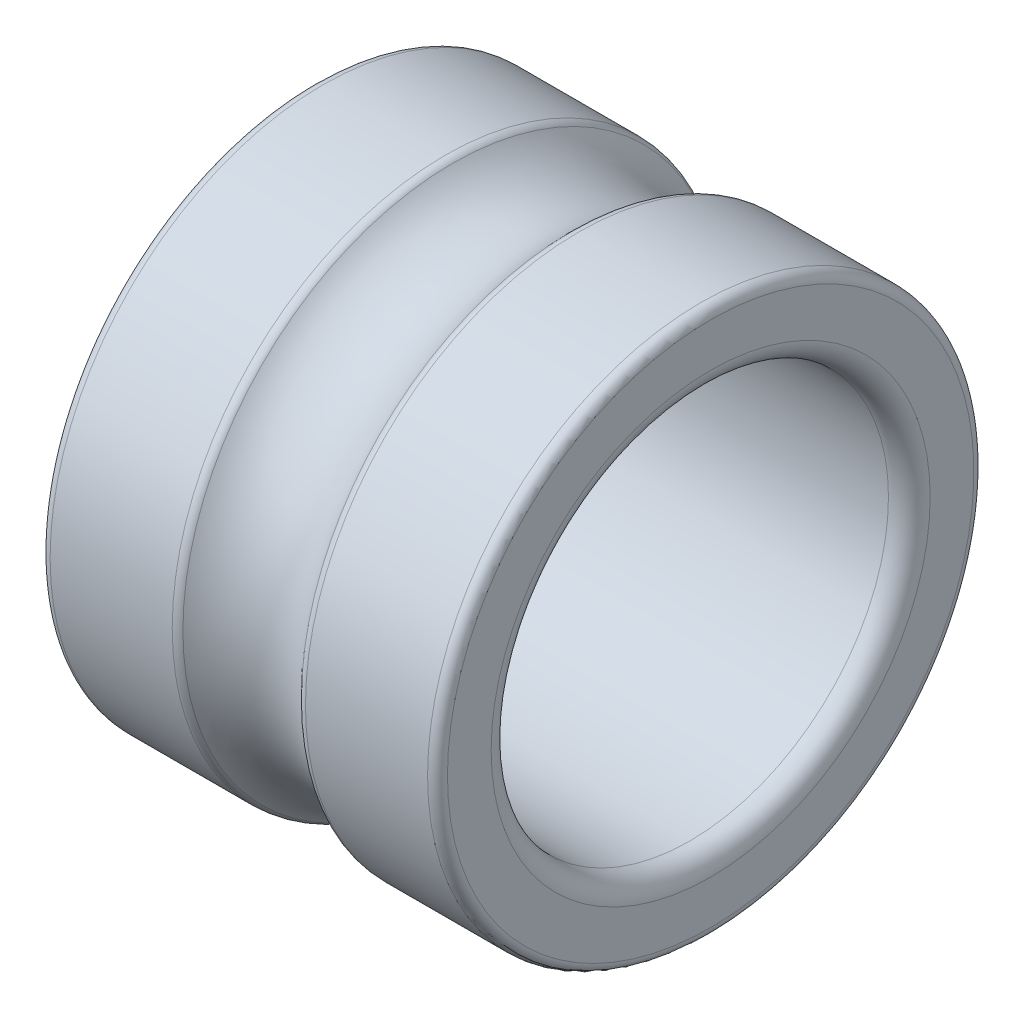
SolidWorks part; units mm, degrees
ref_plane "Front Plane" through (0, 0, 0) normal (0, 0, 1) x (1, 0, 0)
ref_plane "Top Plane" through (0, 0, 0) normal (0, 1, 0) x (1, 0, 0)
ref_plane "Right Plane" through (0, 0, 0) normal (1, 0, 0) x (0, 0, -1)
sketch "Sketch1" plane through (0, 0, 0) normal (0, 0, 1) x (1, 0, 0)
  line L0 (-65.5527, 0) -> (135.7326, 0) construction
  line L1 (0, 20) -> (0, 0) construction
  line L2 (-20, 27.5) -> (-6.245, 27.5)
  line L3 (-20, 27.5) -> (-20, 22.1)
  line L4 (-17.9, 20) -> (17.9, 20)
  line L5 (20, 27.5) -> (20, 22.1)
  line L6 (-20, 27.5) -> (20, 20) construction
  line L7 (-20, 20) -> (20, 27.5) construction
  line L8 (6.245, 27.5) -> (20, 27.5)
  arc A0 (6.245, 27.5) -> (-6.245, 27.5) centre (0, 32.5) cw
  arc A1 (17.9, 20) -> (20, 22.1) centre (17.9, 22.1) ccw
  arc A2 (-20, 22.1) -> (-17.9, 20) centre (-17.9, 22.1) ccw
  point P3 (0, 23.75)
  dimension "D5" = 8
  dimension "D6" = 2.1
  dimension "D1" = 40
  dimension "D2" = 20
  dimension "D3" = 27.5
  dimension "D4" = 5
revolve "Revolve1" add sketch "Sketch1" angle 360 about L0
fillet "Fillet1" radius 1 4 edges at (20, 0, 27.5) (6.245, 0, 27.5) (-6.245, 0, 27.5) (-20, 0, 27.5)
scale "Scale2" scale about centroid uniform scaling yes scale factor 0.1
